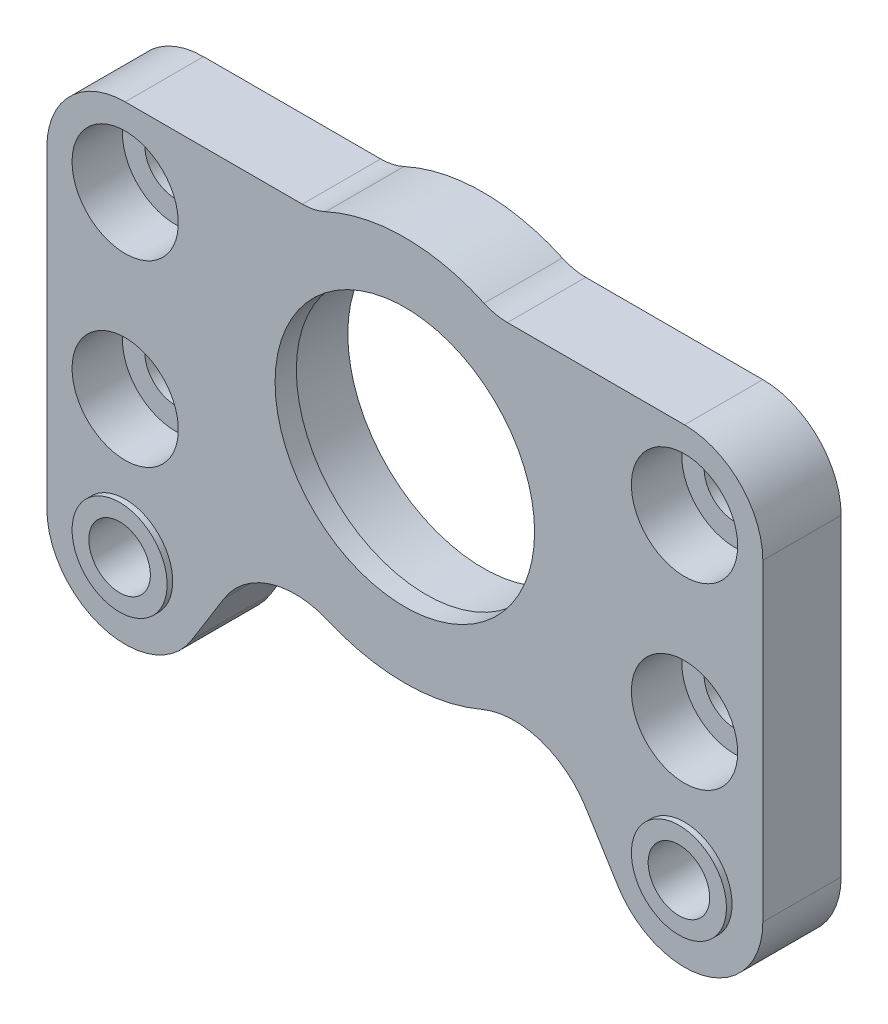
SolidWorks part; units mm, degrees
ref_plane "Front Plane" through (0, 0, 0) normal (0, 0, 1) x (1, 0, 0)
ref_plane "Top Plane" through (0, 0, 0) normal (0, 1, 0) x (1, 0, 0)
ref_plane "Right Plane" through (0, 0, 0) normal (1, 0, 0) x (0, 0, -1)
sketch "Sketch1" plane through (0, 0, 0) normal (0, 0, 1) x (1, 0, 0)
  line L4 (32, 8) -> (32, -20)
  line L7 (0, 0) -> (20.4, 0) construction
  line L8 (19.0514, -23.6897) -> (16.1715, -19.0467)
  line L10 (0, 17) -> (0, 11.6)
  line L11 (8, 15) -> (25, 15)
  line L12 (0, -11.6) -> (0, -17.5)
  line L13 (0, 11.6) -> (0, -11.6) construction
  line L14 (25, 8) -> (25, -20) construction
  arc A0 (0, -11.6) -> (0, 11.6) centre (0, 0) ccw
  arc A1 (8, 15) -> (0, 17) centre (0, 0) ccw
  arc A2 (0, -17.5) -> (6.8586, -16.1) centre (0, 0) ccw
  arc A3 (19.0514, -23.6897) -> (32, -20) centre (25, -20) ccw
  arc A4 (16.1715, -19.0467) -> (6.8586, -16.1) centre (9.798, -23) ccw
  arc A5 (25, 15) -> (32, 8) centre (25, 8) cw
  dimension "D1" = 7
  dimension "D4" = 11.6
  dimension "D5" = 17
  dimension "D6" = 17.5
  dimension "D7" = 7.5
  dimension "D8" = 20
  dimension "D2" = 28
  dimension "D3" = 25
  dimension "D9" = 15
  dimension "D10" = 23
extrude "Boss-Extrude1" add sketch "Sketch1" along normal mid plane 7 separate body
sketch "Sketch3" plane through (0, 0, 3.5) normal (0, 0, 1) x (1, 0, 0)
  line L0 (25, 8) -> (25, -8) construction
  line L1 (25, -8) -> (25, -20) construction
  line L2 (32, -20) -> (32, 8) construction
  line L3 (25, 15) -> (8, 15) construction
  circle A0 centre (25, 8) radius 2.75
  circle A1 centre (25, -8) radius 2.75
  circle A2 centre (25, -20) radius 2.75
  dimension "D1" = 5.5
  dimension "D2" = 16
  dimension "D3" = 12
  dimension "D4" = 7
  dimension "D5" = 7
extrude "Cut-Extrude1" cut sketch "Sketch3" against normal through all both and the other way through all
sketch "Sketch4" plane through (0, 0, -3.5) normal (0, 0, -1) x (-1, 0, 0)
  circle A0 centre (0, 0) radius 12.1
  dimension "D1" = 24.2
extrude "Cut-Extrude2" cut sketch "Sketch4" against normal blind 5.1
sketch "Sketch5" plane through (0, 0, 3.5) normal (0, 0, 1) x (1, 0, 0)
  circle A0 centre (25, -20) radius 2.75 construction
  circle A1 centre (25, -20) radius 2.75
  circle A2 centre (25, -20) radius 4.25
  dimension "D1" = 8.5
extrude "Boss-Extrude2" add sketch "Sketch5" along normal blind 0.5
sketch "Sketch6" plane through (0, 0, 3.5) normal (0, 0, 1) x (1, 0, 0)
  circle A0 centre (25, -8) radius 4.75
  circle A1 centre (25, 8) radius 4.75
  dimension "D1" = 9.5
extrude "Cut-Extrude3" cut sketch "Sketch6" against normal blind 4.5
fillet "Fillet1" radius 5 1 edges at (8, 15, 0)
sketch "Sketch8" plane through (0, 0, -3.5) normal (0, 0, -1) x (-1, 0, 0)
  line L1 (-22.5463, -15.75) -> (-27.4537, -15.75)
  line L2 (-27.4537, -15.75) -> (-29.9075, -20)
  line L3 (-29.9075, -20) -> (-27.4537, -24.25)
  line L4 (-27.4537, -24.25) -> (-22.5463, -24.25)
  line L5 (-22.5463, -24.25) -> (-20.0925, -20)
  line L6 (-20.0925, -20) -> (-22.5463, -15.75)
  circle A0 centre (-25, -20) radius 4.25 construction
  dimension "D1" = 8.5
extrude "Cut-Extrude4" cut sketch "Sketch8" against normal blind 3.5
mirror "Mirror2" about plane through (0, 17, 3.5) normal (1, 0, 0) of bodies 109 102
